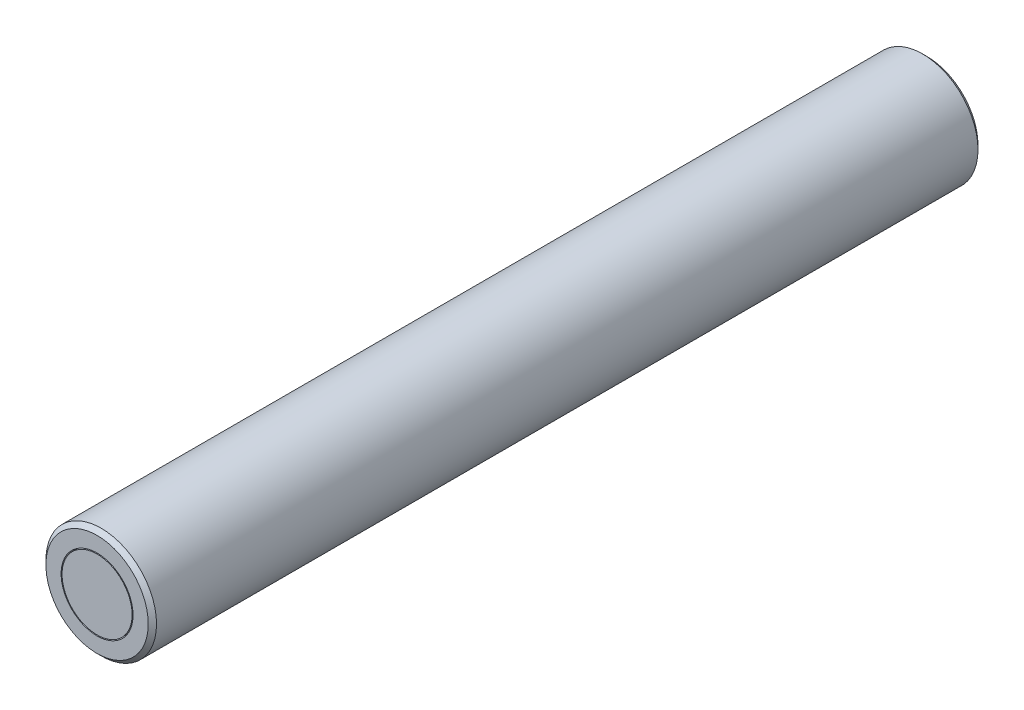
SolidWorks part; units mm, degrees
ref_plane "Front Plane" through (0, 0, 0) normal (0, 0, 1) x (1, 0, 0)
ref_plane "Top Plane" through (0, 0, 0) normal (0, 1, 0) x (1, 0, 0)
ref_plane "Right Plane" through (0, 0, 0) normal (1, 0, 0) x (0, 0, -1)
sketch "Sketch1" plane through (0, 0, 0) normal (0, 0, 1) x (1, 0, 0)
  circle A0 centre (0, 0) radius 2
  dimension "D1" = 4
extrude "Boss-Extrude2" add sketch "Sketch1" along normal blind 30 contours A0
shell "Shell1" thickness 0.7
chamfer "End1 Chamfer" distance 0.15 angle 45 1 edges at (2, 0, 0)
chamfer "End2 Chamfer" distance 0.15 angle 45 1 edges at (2, 0, 30)
sketch "Sketch2" plane through (0, 0, 30) normal (0, 0, 1) x (1, 0, 0)
  circle A0 centre (0, 0) radius 1.2666
  circle A1 centre (0, 0) radius 1.2666
  circle A2 centre (0, 0) radius 1.2666
extrude "Boss-Extrude8" add sketch "Sketch2" against normal through all separate body contours A0
sketch "Sketch3" plane through (0, 0, 30) normal (0, 0, 1) x (1, 0, 0)
  circle A0 centre (0, 0) radius 4
equation "\"ConduitLength\"= 30mm"
equation "\"Outer_Diameter\"= 4mm"
equation "\"Wall_Thickness\"= 0.7mm"
equation "\"Inner Diameter\"= \"Outer_Diameter\" - 2 * \"Wall_Thickness\""
